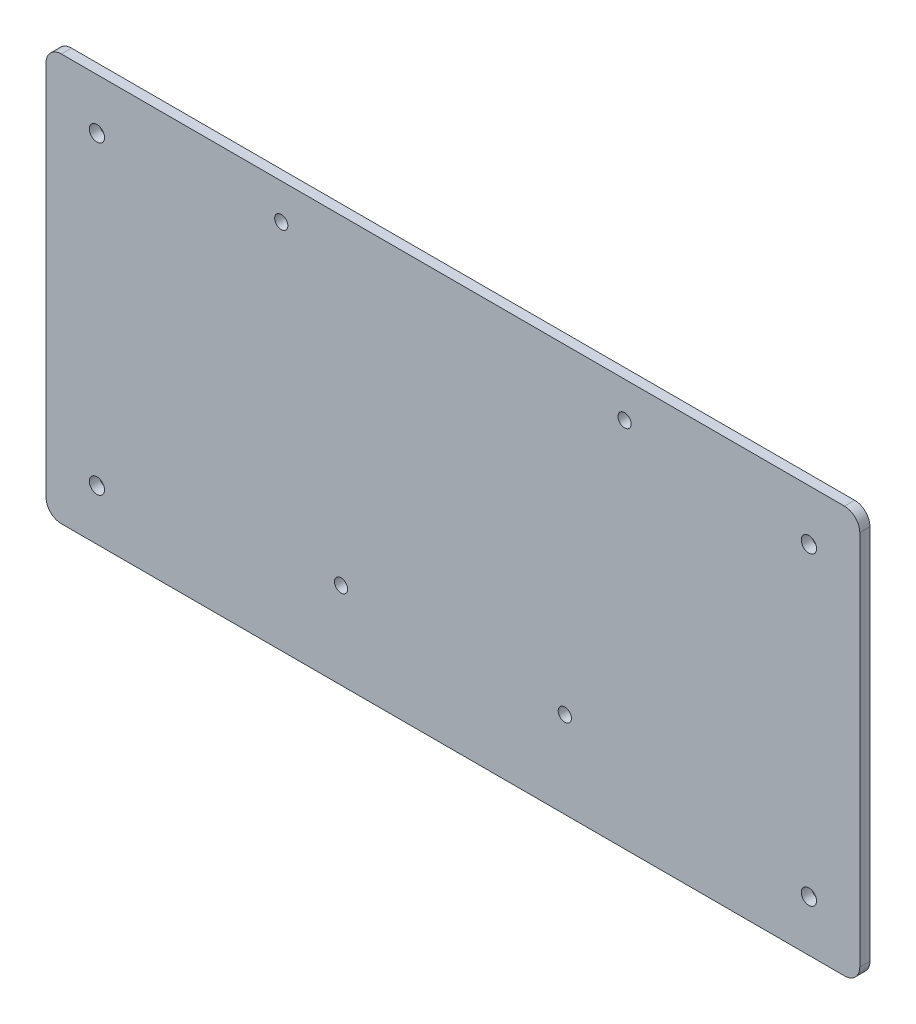
SolidWorks part; units mm, degrees
material "C-玻璃纤维"
ref_plane "前视基准面" through (0, 0, 0) normal (0, 0, 1) x (1, 0, 0)
ref_plane "上视基准面" through (0, 0, 0) normal (0, 1, 0) x (1, 0, 0)
ref_plane "右视基准面" through (0, 0, 0) normal (1, 0, 0) x (0, 0, -1)
other "Configuration Table"
sketch "草图1" plane through (0, 0, 0) normal (0, 0, 1) x (1, 0, 0)
  line L1 (-80, 40) -> (80, 40)
  line L2 (-80, 40) -> (-80, -40)
  line L3 (-80, -40) -> (80, -40)
  line L4 (80, 40) -> (80, -40)
  line L5 (-80, 40) -> (80, -40) construction
  line L6 (-80, -40) -> (80, 40) construction
  point P0 (0, 0)
  dimension "D1" = 160
  dimension "D2" = 80
extrude "凸台-拉伸1" add sketch "草图1" along normal blind 2 contours L2 L1 L4 L3
sketch "草图2" plane through (0, 0, 2) normal (0, 0, 1) x (1, 0, 0)
  line L0 (-80, 40) -> (80, 40) construction
  line L1 (-80, 40) -> (-80, -40) construction
  circle A0 centre (-33.75, 33) radius 1.3
  circle A1 centre (33.75, 33) radius 1.3
  circle A2 centre (-22, -23) radius 1.3
  circle A3 centre (22, -23) radius 1.3
  dimension "D1" = 2.6
  dimension "D3" = 2.6
  dimension "D5" = 67.5
  dimension "D6" = 44
  dimension "D7" = 56
  dimension "D8" = 7
  dimension "D9" = 46.25
  dimension "D10" = 58
  dimension "D2" = 2
  dimension "D4" = 2
extrude "切除-拉伸1" cut sketch "草图2" against normal through all
sketch "草图7" plane through (0, 0, 0) normal (0, 0, -1) x (-1, 0, 0)
  circle A0 centre (-70, -30) radius 1.5
  circle A1 centre (-70, 30) radius 1.5
  circle A2 centre (70, 30) radius 1.5
  circle A3 centre (70, -30) radius 1.5
  dimension "D1" = 3
  dimension "D2" = 3
  dimension "D3" = 3
  dimension "D4" = 3
extrude "切除-拉伸3" cut sketch "草图7" against normal through all
fillet "圆角1" radius 3 4 edges at (80, -40, 1) (-80, -40, 1) (80, 40, 1) (-80, 40, 1)
